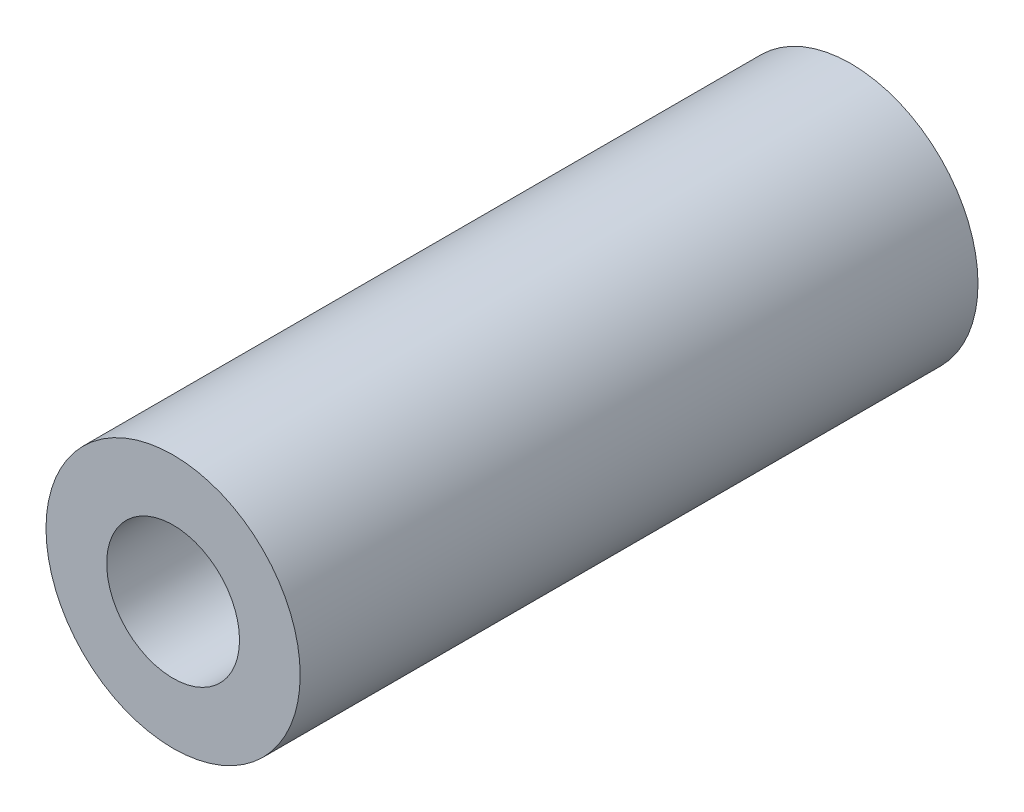
SolidWorks part; units mm, degrees
material "6061-T6 (SS)"
ref_plane "Front Plane" through (0, 0, 0) normal (0, 0, 1) x (1, 0, 0)
ref_plane "Top Plane" through (0, 0, 0) normal (0, 1, 0) x (1, 0, 0)
ref_plane "Right Plane" through (0, 0, 0) normal (1, 0, 0) x (0, 0, -1)
sketch "Sketch1" plane through (0, 0, 0) normal (0, 0, 1) x (1, 0, 0)
  circle A0 centre (0, 0) radius 4.7625
  circle A1 centre (0, 0) radius 2.4892
  dimension "D1" = 9.525
  dimension "D2" = 4.9784
extrude "Boss-Extrude1" add sketch "Sketch1" along normal blind 25.4 contours A0 A1
